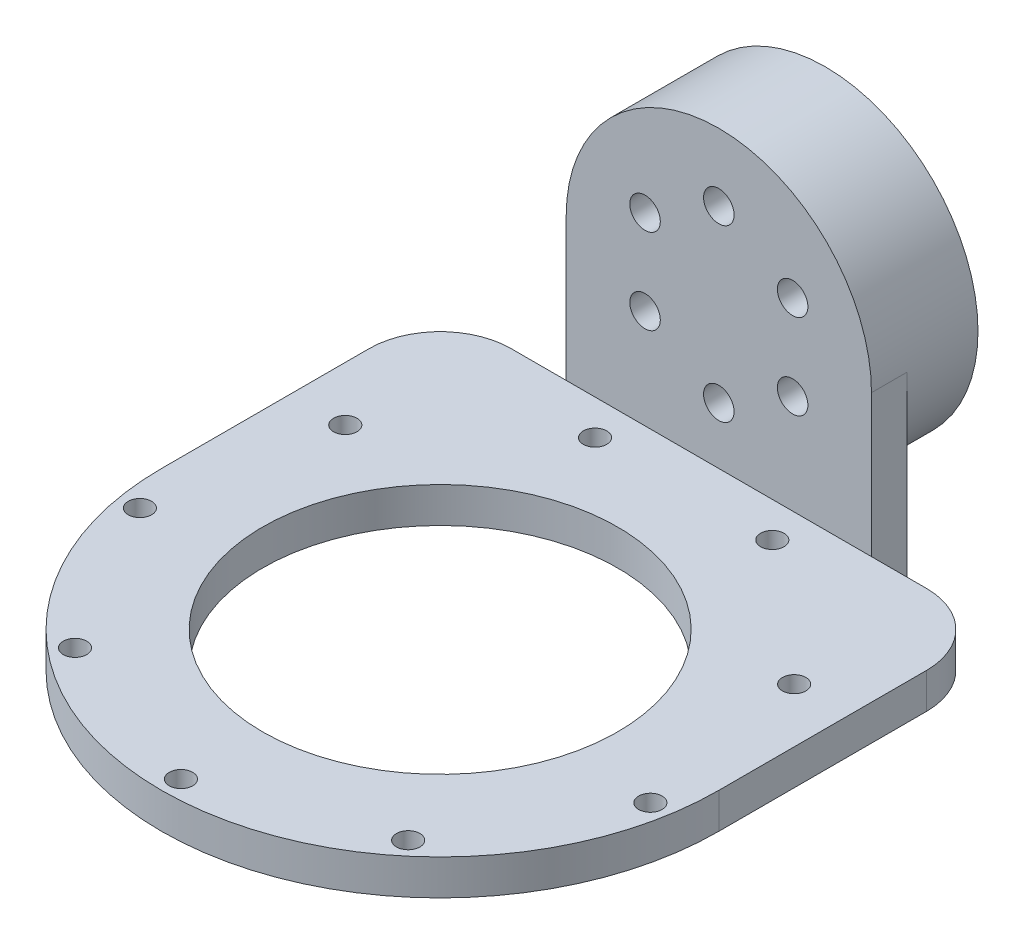
SolidWorks part; units mm, degrees
material "ABS"
ref_plane "正面" through (0, 0, 0) normal (0, 0, 1) x (1, 0, 0)
ref_plane "平面" through (0, 0, 0) normal (0, 1, 0) x (1, 0, 0)
ref_plane "右側面" through (0, 0, 0) normal (1, 0, 0) x (0, 0, -1)
sketch "ｽｹｯﾁ1" plane through (0, 0, 0) normal (0, 0, 1) x (1, 0, 0)
  circle A0 centre (0, 0) radius 21.5
  dimension "D1" = 43
extrude "ﾎﾞｽ - 押し出し1" add sketch "ｽｹｯﾁ1" along normal blind 10
sketch "ｽｹｯﾁ2" plane through (0, 0, 10) normal (0, 0, 1) x (1, 0, 0)
  line L0 (-21.5, 0) -> (-21.5, -25)
  line L1 (21.5, 0) -> (21.5, -25)
  line L2 (21.5, -25) -> (-21.5, -25)
  line L3 (21.5, 0) -> (-21.5, 0) construction
  arc A0 (21.5, 0) -> (-21.5, 0) centre (0, 0) ccw
  circle A1 centre (0, 0) radius 21.5 construction
  dimension "D1" = 25
extrude "ﾎﾞｽ - 押し出し2" add sketch "ｽｹｯﾁ2" along normal blind 5
sketch "ｽｹｯﾁ3" plane through (0, -25, 0) normal (0, -1, 0) x (1, 0, 0)
  line L0 (-21.5, 15) -> (21.5, 15) construction
  line L1 (-39.25, 54.25) -> (-39.25, 15)
  line L2 (-39.25, 15) -> (39.25, 15)
  line L3 (39.25, 15) -> (39.25, 54.25)
  arc A0 (39.25, 54.25) -> (-39.25, 54.25) centre (0, 54.25) ccw
  point P1 (0, 15)
  dimension "D1" = 78.5
extrude "ﾎﾞｽ - 押し出し3" add sketch "ｽｹｯﾁ3" against normal blind 5
fillet "ﾌｨﾚｯﾄ1" radius 10 2 edges at (-39.25, -22.5, 15) (39.25, -22.5, 15)
sketch "ｽｹｯﾁ4" plane through (0, -20, 0) normal (0, 1, 0) x (1, 0, 0)
  line L0 (-39.25, -54.25) -> (39.25, -54.25) construction
  circle A0 centre (0, -54.25) radius 25
  dimension "D1" = 50
extrude "ｶｯﾄ - 押し出し1" cut sketch "ｽｹｯﾁ4" against normal through all
sketch "ｽｹｯﾁ5" plane through (0, -20, 0) normal (0, 1, 0) x (1, 0, 0)
  line L0 (0, -54.25) -> (0, -93.5) construction
  arc A0 (-39.25, -54.25) -> (39.25, -54.25) centre (0, -54.25) ccw construction
  circle A1 centre (0, -90.75) radius 1.65
  circle A2 centre (-23.4617, -82.2106) radius 1.65
  circle A3 centre (-35.9455, -60.5882) radius 1.65
  circle A4 centre (-31.6099, -36) radius 1.65
  circle A5 centre (-12.4837, -19.9512) radius 1.65
  circle A6 centre (12.4837, -19.9512) radius 1.65
  circle A7 centre (31.6099, -36) radius 1.65
  circle A8 centre (35.9455, -60.5882) radius 1.65
  circle A9 centre (23.4617, -82.2106) radius 1.65
  point P27 (0, -54.25)
  dimension "D1" = 3.3
  dimension "D2" = 36.5
  dimension "D3" = 9
extrude "ｶｯﾄ - 押し出し2" cut sketch "ｽｹｯﾁ5" against normal through all
sketch "ｽｹｯﾁ6" plane through (0, 0, 15) normal (0, 0, 1) x (1, 0, 0)
  line L0 (0, 0) -> (0, 12) construction
  circle A0 centre (0, 12) radius 2.15
  circle A1 centre (10.3923, 6) radius 2.15
  circle A2 centre (10.3923, -6) radius 2.15
  circle A3 centre (0, -12) radius 2.15
  circle A4 centre (-10.3923, -6) radius 2.15
  circle A5 centre (-10.3923, 6) radius 2.15
  point P17 (0, 0)
  dimension "D1" = 4.3
  dimension "D3" = 12
  dimension "D2" = 6
extrude "ｶｯﾄ - 押し出し3" cut sketch "ｽｹｯﾁ6" against normal through all
